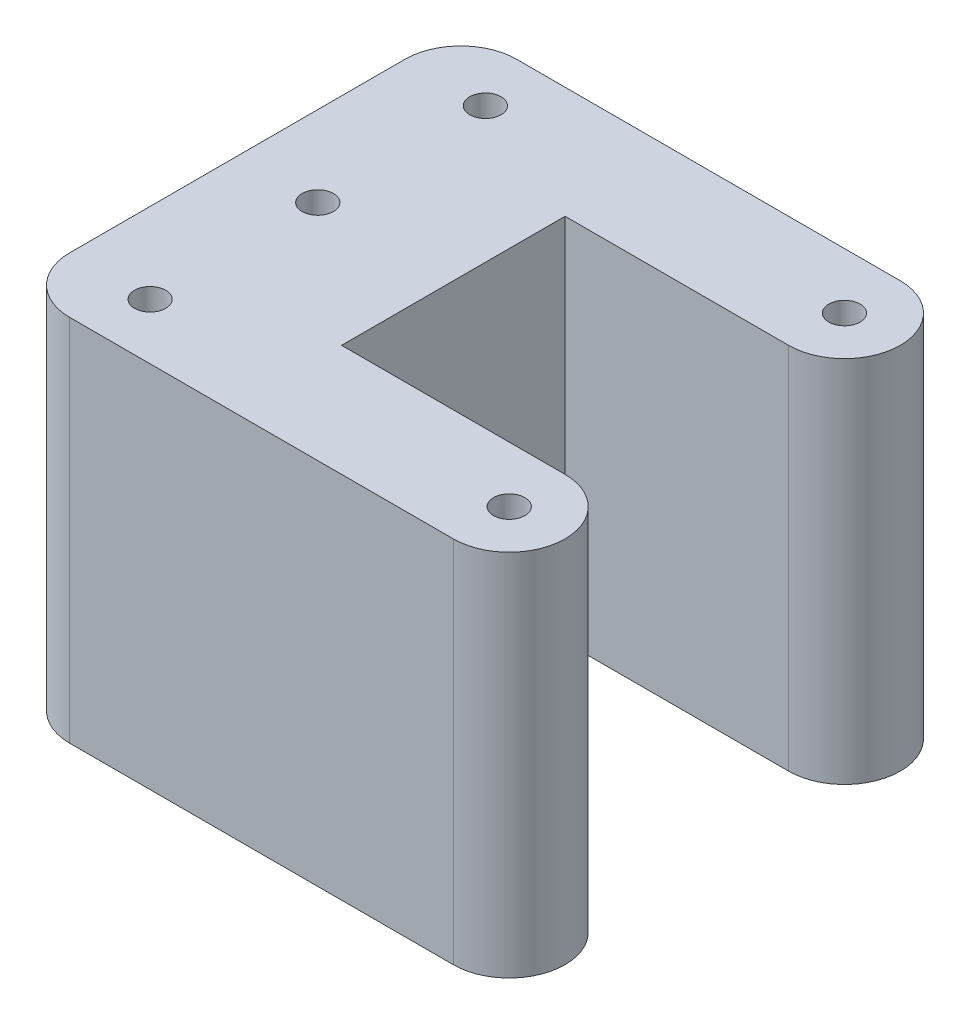
SolidWorks part; units mm, degrees
ref_plane "前视基准面" through (0, 0, 0) normal (0, 0, 1) x (1, 0, 0)
ref_plane "上视基准面" through (0, 0, 0) normal (0, 1, 0) x (1, 0, 0)
ref_plane "右视基准面" through (0, 0, 0) normal (1, 0, 0) x (0, 0, -1)
sketch "草图1" plane through (0, 0, 0) normal (0, 1, 0) x (1, 0, 0)
  line L13 (63.5392, -45.5416) -> (63.5392, -25.5416)
  line L32 (44.2055, -20.5416) -> (44.2055, -50.5416)
  line L33 (49.2055, -15.5416) -> (83.5392, -15.5416)
  line L34 (49.2055, -55.5416) -> (83.5392, -55.5416)
  line L35 (63.5392, -25.5416) -> (83.5392, -25.5416)
  line L36 (63.5392, -45.5416) -> (83.5392, -45.5416)
  circle A32 centre (83.5392, -20.5416) radius 1.4
  arc A33 (83.5392, -15.5416) -> (83.5392, -25.5416) centre (83.5392, -20.5416) cw
  arc A34 (83.5392, -55.5416) -> (83.5392, -45.5416) centre (83.5392, -50.5416) ccw
  circle A35 centre (83.5392, -50.5416) radius 1.4
  circle A36 centre (51.4061, -20.5416) radius 1.4
  circle A37 centre (51.4061, -35.5416) radius 1.4
  circle A38 centre (51.4061, -50.5416) radius 1.4
  arc A39 (49.2055, -15.5416) -> (44.2055, -20.5416) centre (49.2055, -20.5416) ccw
  arc A40 (49.2055, -55.5416) -> (44.2055, -50.5416) centre (49.2055, -50.5416) cw
  dimension "D1" = 5
  dimension "D2" = 5
extrude "凸台-拉伸1" add sketch "草图1" along normal blind 33
